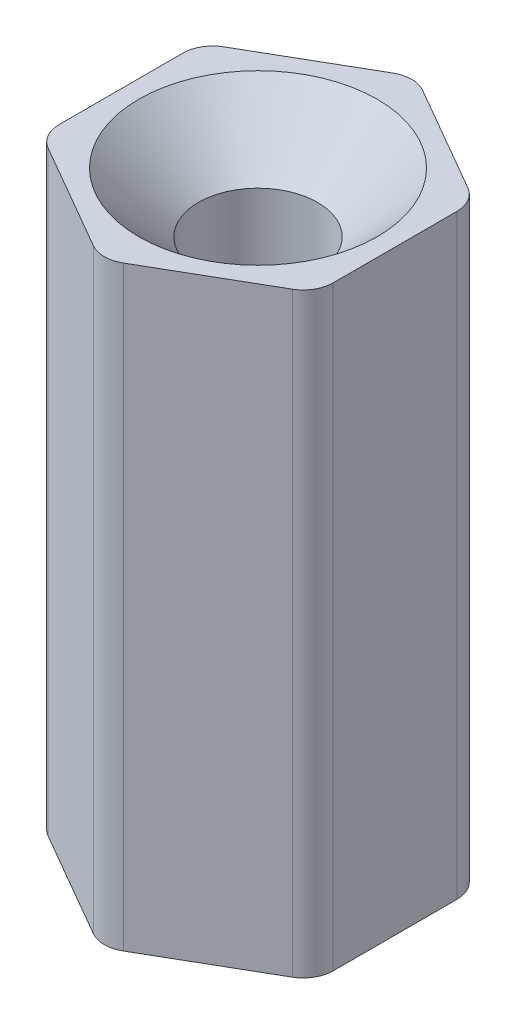
SolidWorks part; units mm, degrees
material "Free-Cutting Brass, UNS C36000"
ref_plane "Front" through (0, 0, 0) normal (0, 0, 1) x (1, 0, 0)
ref_plane "Top" through (0, 0, 0) normal (0, 1, 0) x (1, 0, 0)
ref_plane "Right" through (0, 0, 0) normal (1, 0, 0) x (0, 0, -1)
sketch "Sketch1" plane through (0, 0, 0) normal (0, 1, 0) x (1, 0, 0)
  line L1 (0, 2.6558) -> (-2.3, 1.3279)
  line L2 (-2.3, 1.3279) -> (-2.3, -1.3279)
  line L3 (-2.3, -1.3279) -> (0, -2.6558)
  line L4 (0, -2.6558) -> (2.3, -1.3279)
  line L5 (2.3, -1.3279) -> (2.3, 1.3279)
  line L6 (2.3, 1.3279) -> (0, 2.6558)
  circle A0 centre (0, 0) radius 2.3 construction
  dimension "D1" = 4.6
extrude "Boss-Extrude1" add sketch "Sketch1" along normal blind 10
sketch "Sketch2" plane through (0, 10, 0) normal (0, 1, 0) x (1, 0, 0)
  circle A0 centre (0, 0) radius 1
  dimension "D1" = 2
extrude "Cut-Extrude1" cut sketch "Sketch2" against normal through all
chamfer "Chamfer2" distance 1 angle 45 2 edges at (0, 0, 1) (0, 10, 1)
fillet "Fillet1" radius 0.5 6 edges at (0, 5, 2.6558) (-2.3, 5, 1.3279) (-2.3, 5, -1.3279) (0, 5, -2.6558) (2.3, 5, -1.3279) (2.3, 5, 1.3279)
